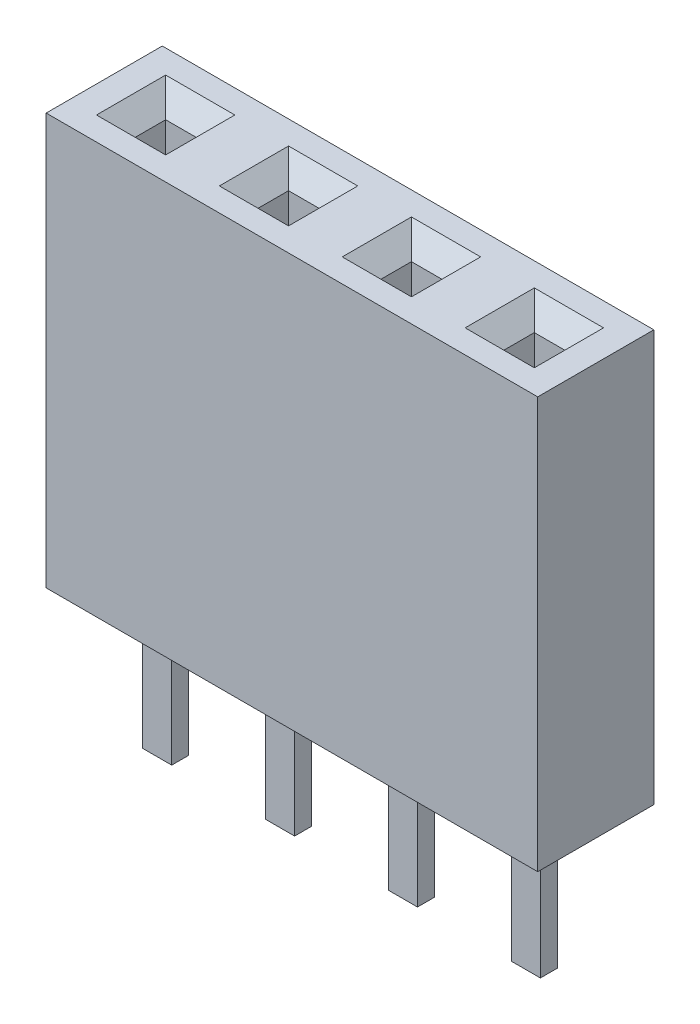
SolidWorks part; units mm, degrees
ref_plane "Front Plane" through (0, 0, 0) normal (0, 0, 1) x (1, 0, 0)
ref_plane "Top Plane" through (0, 0, 0) normal (0, 1, 0) x (1, 0, 0)
ref_plane "Right Plane" through (0, 0, 0) normal (1, 0, 0) x (0, 0, -1)
sketch "Sketch1" plane through (0, 0, 0) normal (0, 1, 0) x (1, 0, 0)
  line L1 (19.05, -1.2) -> (-19.05, -1.2)
  line L2 (19.05, -1.2) -> (19.05, 1.2)
  line L3 (19.05, 1.2) -> (-19.05, 1.2)
  line L4 (-19.05, -1.2) -> (-19.05, 1.2)
  line L5 (19.05, -1.2) -> (-19.05, 1.2) construction
  line L6 (19.05, 1.2) -> (-19.05, -1.2) construction
  point P0 (0, 0)
  dimension "D1" = 2.4
  dimension "D2" = 38.1
extrude "Boss-Extrude1" add sketch "Sketch1" along normal blind 8.5
sketch "Sketch2" plane through (0, 8.5, 0) normal (0, 1, 0) x (1, 0, 0)
  line L0 (-19.05, 0) -> (19.05, 0) construction
  line L1 (-19.05, 1.2) -> (-19.05, -1.2) construction
  line L2 (19.05, -1.2) -> (19.05, 1.2) construction
  line L3 (-15.555, 0.315) -> (-14.925, 0.315)
  line L4 (-18.095, -0.315) -> (-17.465, -0.315)
  line L5 (-18.095, -0.315) -> (-18.095, 0.315)
  line L6 (-18.095, 0.315) -> (-17.465, 0.315)
  line L7 (-17.465, -0.315) -> (-17.465, 0.315)
  line L8 (-18.095, -0.315) -> (-17.465, 0.315) construction
  line L9 (-18.095, 0.315) -> (-17.465, -0.315) construction
  line L10 (-15.555, -0.315) -> (-15.555, 0.315)
  line L11 (-15.555, -0.315) -> (-14.925, -0.315)
  line L12 (-14.925, -0.315) -> (-14.925, 0.315)
  line L13 (-13.015, 0.315) -> (-12.385, 0.315)
  line L14 (-13.015, -0.315) -> (-13.015, 0.315)
  line L15 (-13.015, -0.315) -> (-12.385, -0.315)
  line L16 (-12.385, -0.315) -> (-12.385, 0.315)
  line L17 (-10.475, 0.315) -> (-9.845, 0.315)
  line L18 (-10.475, -0.315) -> (-10.475, 0.315)
  line L19 (-10.475, -0.315) -> (-9.845, -0.315)
  line L20 (-9.845, -0.315) -> (-9.845, 0.315)
  line L21 (-7.935, 0.315) -> (-7.305, 0.315)
  line L22 (-7.935, -0.315) -> (-7.935, 0.315)
  line L23 (-7.935, -0.315) -> (-7.305, -0.315)
  line L24 (-7.305, -0.315) -> (-7.305, 0.315)
  line L25 (-5.395, 0.315) -> (-4.765, 0.315)
  line L26 (-5.395, -0.315) -> (-5.395, 0.315)
  line L27 (-5.395, -0.315) -> (-4.765, -0.315)
  line L28 (-4.765, -0.315) -> (-4.765, 0.315)
  line L29 (-2.855, 0.315) -> (-2.225, 0.315)
  line L30 (-2.855, -0.315) -> (-2.855, 0.315)
  line L31 (-2.855, -0.315) -> (-2.225, -0.315)
  line L32 (-2.225, -0.315) -> (-2.225, 0.315)
  line L33 (-0.315, 0.315) -> (0.315, 0.315)
  line L34 (-0.315, -0.315) -> (-0.315, 0.315)
  line L35 (-0.315, -0.315) -> (0.315, -0.315)
  line L36 (0.315, -0.315) -> (0.315, 0.315)
  line L37 (2.225, 0.315) -> (2.855, 0.315)
  line L38 (2.225, -0.315) -> (2.225, 0.315)
  line L39 (2.225, -0.315) -> (2.855, -0.315)
  line L40 (2.855, -0.315) -> (2.855, 0.315)
  line L41 (4.765, 0.315) -> (5.395, 0.315)
  line L42 (4.765, -0.315) -> (4.765, 0.315)
  line L43 (4.765, -0.315) -> (5.395, -0.315)
  line L44 (5.395, -0.315) -> (5.395, 0.315)
  line L45 (7.305, 0.315) -> (7.935, 0.315)
  line L46 (7.305, -0.315) -> (7.305, 0.315)
  line L47 (7.305, -0.315) -> (7.935, -0.315)
  line L48 (7.935, -0.315) -> (7.935, 0.315)
  line L49 (9.845, 0.315) -> (10.475, 0.315)
  line L50 (9.845, -0.315) -> (9.845, 0.315)
  line L51 (9.845, -0.315) -> (10.475, -0.315)
  line L52 (10.475, -0.315) -> (10.475, 0.315)
  line L53 (12.385, 0.315) -> (13.015, 0.315)
  line L54 (12.385, -0.315) -> (12.385, 0.315)
  line L55 (12.385, -0.315) -> (13.015, -0.315)
  line L56 (13.015, -0.315) -> (13.015, 0.315)
  line L57 (14.925, 0.315) -> (15.555, 0.315)
  line L58 (14.925, -0.315) -> (14.925, 0.315)
  line L59 (14.925, -0.315) -> (15.555, -0.315)
  line L60 (15.555, -0.315) -> (15.555, 0.315)
  line L61 (17.465, 0.315) -> (18.095, 0.315)
  line L62 (17.465, -0.315) -> (17.465, 0.315)
  line L63 (17.465, -0.315) -> (18.095, -0.315)
  line L64 (18.095, -0.315) -> (18.095, 0.315)
  point P6 (-17.78, 0)
  dimension "D1" = 0.63
  dimension "D2" = 0.63
  dimension "D3" = 1.27
  dimension "D4" = 15
extrude "Cut-Extrude1" cut sketch "Sketch2" against normal blind 6.5
sketch "Sketch3" plane through (0, 0, 0) normal (0, -1, 0) x (1, 0, 0)
  line L0 (-19.05, 0) -> (19.05, 0) construction
  line L1 (-19.05, -1.2) -> (-19.05, 1.2) construction
  line L2 (19.05, 1.2) -> (19.05, -1.2) construction
  line L3 (-15.54, 0.175) -> (-14.94, 0.175)
  line L4 (-18.08, -0.175) -> (-17.48, -0.175)
  line L5 (-18.08, -0.175) -> (-18.08, 0.175)
  line L6 (-18.08, 0.175) -> (-17.48, 0.175)
  line L7 (-17.48, -0.175) -> (-17.48, 0.175)
  line L8 (-18.08, -0.175) -> (-17.48, 0.175) construction
  line L9 (-18.08, 0.175) -> (-17.48, -0.175) construction
  line L10 (-15.54, -0.175) -> (-15.54, 0.175)
  line L11 (-15.54, -0.175) -> (-14.94, -0.175)
  line L12 (-14.94, -0.175) -> (-14.94, 0.175)
  line L13 (-13, 0.175) -> (-12.4, 0.175)
  line L14 (-13, -0.175) -> (-13, 0.175)
  line L15 (-13, -0.175) -> (-12.4, -0.175)
  line L16 (-12.4, -0.175) -> (-12.4, 0.175)
  line L17 (-10.46, 0.175) -> (-9.86, 0.175)
  line L18 (-10.46, -0.175) -> (-10.46, 0.175)
  line L19 (-10.46, -0.175) -> (-9.86, -0.175)
  line L20 (-9.86, -0.175) -> (-9.86, 0.175)
  line L21 (-7.92, 0.175) -> (-7.32, 0.175)
  line L22 (-7.92, -0.175) -> (-7.92, 0.175)
  line L23 (-7.92, -0.175) -> (-7.32, -0.175)
  line L24 (-7.32, -0.175) -> (-7.32, 0.175)
  line L25 (-5.38, 0.175) -> (-4.78, 0.175)
  line L26 (-5.38, -0.175) -> (-5.38, 0.175)
  line L27 (-5.38, -0.175) -> (-4.78, -0.175)
  line L28 (-4.78, -0.175) -> (-4.78, 0.175)
  line L29 (-2.84, 0.175) -> (-2.24, 0.175)
  line L30 (-2.84, -0.175) -> (-2.84, 0.175)
  line L31 (-2.84, -0.175) -> (-2.24, -0.175)
  line L32 (-2.24, -0.175) -> (-2.24, 0.175)
  line L33 (-0.3, 0.175) -> (0.3, 0.175)
  line L34 (-0.3, -0.175) -> (-0.3, 0.175)
  line L35 (-0.3, -0.175) -> (0.3, -0.175)
  line L36 (0.3, -0.175) -> (0.3, 0.175)
  line L37 (2.24, 0.175) -> (2.84, 0.175)
  line L38 (2.24, -0.175) -> (2.24, 0.175)
  line L39 (2.24, -0.175) -> (2.84, -0.175)
  line L40 (2.84, -0.175) -> (2.84, 0.175)
  line L41 (4.78, 0.175) -> (5.38, 0.175)
  line L42 (4.78, -0.175) -> (4.78, 0.175)
  line L43 (4.78, -0.175) -> (5.38, -0.175)
  line L44 (5.38, -0.175) -> (5.38, 0.175)
  line L45 (7.32, 0.175) -> (7.92, 0.175)
  line L46 (7.32, -0.175) -> (7.32, 0.175)
  line L47 (7.32, -0.175) -> (7.92, -0.175)
  line L48 (7.92, -0.175) -> (7.92, 0.175)
  line L49 (9.86, 0.175) -> (10.46, 0.175)
  line L50 (9.86, -0.175) -> (9.86, 0.175)
  line L51 (9.86, -0.175) -> (10.46, -0.175)
  line L52 (10.46, -0.175) -> (10.46, 0.175)
  line L53 (12.4, 0.175) -> (13, 0.175)
  line L54 (12.4, -0.175) -> (12.4, 0.175)
  line L55 (12.4, -0.175) -> (13, -0.175)
  line L56 (13, -0.175) -> (13, 0.175)
  line L57 (14.94, 0.175) -> (15.54, 0.175)
  line L58 (14.94, -0.175) -> (14.94, 0.175)
  line L59 (14.94, -0.175) -> (15.54, -0.175)
  line L60 (15.54, -0.175) -> (15.54, 0.175)
  line L61 (17.48, 0.175) -> (18.08, 0.175)
  line L62 (17.48, -0.175) -> (17.48, 0.175)
  line L63 (17.48, -0.175) -> (18.08, -0.175)
  line L64 (18.08, -0.175) -> (18.08, 0.175)
  point P6 (-17.78, 0)
  dimension "D1" = 0.35
  dimension "D2" = 0.6
  dimension "D3" = 1.27
  dimension "D4" = 15
extrude "Boss-Extrude2" add sketch "Sketch3" along normal blind 2.9
chamfer "Chamfer1" distance 0.4 angle 45 60 edges at (0, 8.5, 0.315) (0.315, 8.5, 0) (0, 8.5, -0.315) (-0.315, 8.5, 0) (-2.54, 8.5, 0.315) (-2.225, 8.5, 0) (-2.54, 8.5, -0.315) (-2.855, 8.5, 0) (-5.08, 8.5, 0.315) (-4.765, 8.5, 0) (-5.08, 8.5, -0.315) (-5.395, 8.5, 0) (-7.62, 8.5, 0.315) (-7.305, 8.5, 0) (-7.62, 8.5, -0.315) (-7.935, 8.5, 0) (-10.16, 8.5, 0.315) (-9.845, 8.5, 0) (-10.16, 8.5, -0.315) (-10.475, 8.5, 0) (-12.385, 8.5, 0) (-12.7, 8.5, -0.315) (-13.015, 8.5, 0) (-12.7, 8.5, 0.315) (-15.24, 8.5, 0.315) (-14.925, 8.5, 0) (-15.24, 8.5, -0.315) (-15.555, 8.5, 0) (-17.78, 8.5, 0.315) (-17.465, 8.5, 0) (-17.78, 8.5, -0.315) (-18.095, 8.5, 0) (17.78, 8.5, 0.315) (18.095, 8.5, 0) (17.78, 8.5, -0.315) (17.465, 8.5, 0) (15.24, 8.5, 0.315) (15.555, 8.5, 0) (15.24, 8.5, -0.315) (14.925, 8.5, 0) (12.385, 8.5, 0) (12.7, 8.5, 0.315) (13.015, 8.5, 0) (12.7, 8.5, -0.315) (9.845, 8.5, 0) (10.16, 8.5, 0.315) (10.475, 8.5, 0) (10.16, 8.5, -0.315) (7.305, 8.5, 0) (7.62, 8.5, 0.315) (7.935, 8.5, 0) (7.62, 8.5, -0.315) (4.765, 8.5, 0) (5.08, 8.5, 0.315) (5.395, 8.5, 0) (5.08, 8.5, -0.315) (2.225, 8.5, 0) (2.54, 8.5, -0.315) (2.855, 8.5, 0) (2.54, 8.5, 0.315)
sketch "Sketch4" plane through (0, 8.5, 0) normal (0, 1, 0) x (1, 0, 0)
  line L0 (5.395, 0) -> (7.305, 0) construction
  line L3 (6.35, 0) -> (6.35, 2.1388) construction
  line L4 (5.395, -0.315) -> (5.395, 0.315) construction
  line L5 (6.35, 2.1388) -> (25.7288, 2.1388)
  line L6 (6.35, 2.1388) -> (6.35, -2.3327)
  line L7 (6.35, -2.3327) -> (25.7288, -2.3327)
  line L8 (25.7288, 2.1388) -> (25.7288, -2.3327)
  line L9 (7.305, 0.315) -> (7.305, -0.315) construction
  point P11 (6.35, 0)
extrude "Cut-Extrude2" cut sketch "Sketch4" against normal through all
sketch "Sketch5" plane through (0, 0, 0) normal (0, -1, 0) x (-1, 0, 0)
  line L0 (17.78, -1.2) -> (17.78, 1.2) construction
  line L1 (19.05, -1.2) -> (-6.35, -1.2) construction
  line L2 (-6.35, 1.2) -> (19.05, 1.2) construction
  line L3 (18.08, 0) -> (17.48, 0) construction
  line L4 (18.08, -0.175) -> (18.08, 0.175) construction
  line L5 (17.48, 0.175) -> (17.48, -0.175) construction
  point P12 (17.78, 0)
sketch "Sketch6" plane through (0, 8.5, 0) normal (0, 1, 0) x (1, 0, 0)
  line L0 (-18.495, 0) -> (-17.065, 0) construction
  line L1 (-18.495, -0.715) -> (-18.495, 0.715) construction
  line L2 (-17.065, 0.715) -> (-17.065, -0.715) construction
  line L3 (4.365, 0) -> (5.795, 0) construction
  line L4 (4.365, -0.715) -> (4.365, 0.715) construction
  line L5 (5.795, 0.715) -> (5.795, -0.715) construction
  point P12 (-17.78, 0)
  point P13 (5.08, 0)
sketch "Sketch7" plane through (0, 0, 1.2) normal (0, 0, 1) x (1, 0, 0)
  line L1 (-19.05, 8.5) -> (-3.81, 8.5)
  line L2 (-19.05, 8.5) -> (-19.05, -3.8637)
  line L3 (-19.05, -3.8637) -> (-3.81, -3.8637)
  line L4 (-3.81, 8.5) -> (-3.81, -3.8637)
  dimension "D1" = 15.24
extrude "Cut-Extrude3" cut sketch "Sketch7" against normal through all
